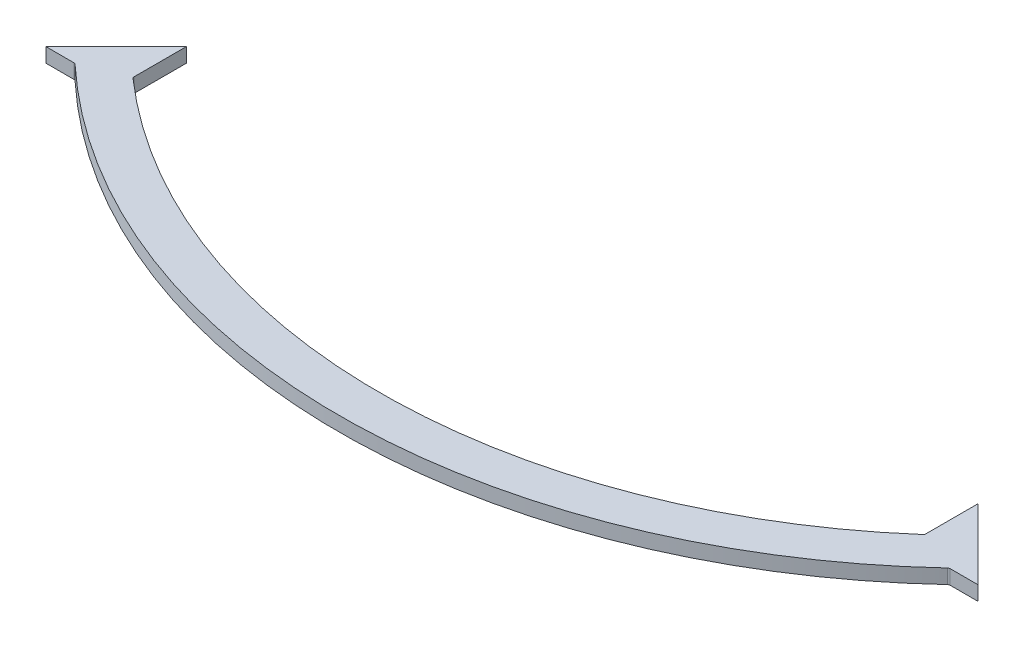
SolidWorks part; units mm, degrees
material "Pine"
ref_plane "Front Plane" through (0, 0, 0) normal (0, 0, 1) x (1, 0, 0)
ref_plane "Top Plane" through (0, 0, 0) normal (0, 1, 0) x (1, 0, 0)
ref_plane "Right Plane" through (0, 0, 0) normal (1, 0, 0) x (0, 0, -1)
sketch "Sketch1" plane through (0, 0, 0) normal (0, 1, 0) x (1, 0, 0)
  line L0 (844.55, 590.55) -> (844.55, -590.55)
  line L1 (-590.55, 862.0125) -> (590.55, 862.0125)
  line L2 (-590.55, 862.0125) -> (-590.55, -862.0125)
  line L3 (-590.55, -862.0125) -> (590.55, -862.0125)
  line L4 (590.55, 862.0125) -> (590.55, -862.0125)
  line L5 (-590.55, 862.0125) -> (590.55, -862.0125) construction
  line L6 (-590.55, -862.0125) -> (590.55, 862.0125) construction
  line L7 (-862.0125, -590.55) -> (862.0125, -590.55)
  line L8 (-862.0125, -590.55) -> (-862.0125, 590.55)
  line L9 (-862.0125, 590.55) -> (862.0125, 590.55)
  line L10 (862.0125, -590.55) -> (862.0125, 590.55)
  line L11 (-862.0125, -590.55) -> (862.0125, 590.55) construction
  line L12 (-862.0125, 590.55) -> (862.0125, -590.55) construction
  circle A0 centre (0, 0) radius 809.625
  circle A1 centre (0, 0) radius 758.825
  dimension "D1" = 1619.25
  dimension "D2" = 50.8
  dimension "D3" = 1181.1
  dimension "D4" = 862.0125
  dimension "D5" = 17.4625
sketch "Sketch2" plane through (0, 0, 0) normal (0, 1, 0) x (1, 0, 0)
  line L0 (546.1, -501.65) -> (546.1, -590.55) construction
  line L13 (590.55, -590.55) -> (501.65, -590.55)
  line L14 (590.55, -590.55) -> (590.55, -501.65)
  line L15 (590.55, -501.65) -> (501.65, -501.65)
  line L16 (501.65, -590.55) -> (501.65, -501.65)
  line L17 (590.55, 862.0125) -> (590.55, -862.0125) construction
  line L18 (501.65, -546.1) -> (590.55, -546.1) construction
  line L19 (-862.0125, -590.55) -> (862.0125, -590.55) construction
  line L20 (-501.65, -590.55) -> (-501.65, -501.65)
  line L21 (-590.55, -501.65) -> (-501.65, -501.65)
  line L22 (-590.55, -590.55) -> (-590.55, -501.65)
  line L23 (-590.55, -590.55) -> (-501.65, -590.55)
  line L24 (-501.65, -546.1) -> (-590.55, -546.1) construction
  line L25 (-546.1, -501.65) -> (-546.1, -590.55) construction
  line L26 (-590.55, 501.65) -> (-501.65, 501.65)
  line L27 (-501.65, 590.55) -> (-501.65, 501.65)
  line L28 (-590.55, 590.55) -> (-501.65, 590.55)
  line L29 (-590.55, 590.55) -> (-590.55, 501.65)
  line L30 (-546.1, 501.65) -> (-546.1, 590.55) construction
  line L31 (-501.65, 546.1) -> (-590.55, 546.1) construction
  line L32 (501.65, 590.55) -> (501.65, 501.65)
  line L33 (590.55, 501.65) -> (501.65, 501.65)
  line L34 (590.55, 590.55) -> (590.55, 501.65)
  line L35 (590.55, 590.55) -> (501.65, 590.55)
  line L36 (501.65, 546.1) -> (590.55, 546.1) construction
  line L37 (546.1, 501.65) -> (546.1, 590.55) construction
  circle A0 centre (0, 0) radius 784.225
  circle A1 centre (0, 0) radius 758.825 construction
  circle A2 centre (0, 0) radius 784.225
  circle A3 centre (0, 0) radius 784.225
  circle A4 centre (0, 0) radius 784.225
  point P24 (546.1, -546.1)
  point P48 (0, 0)
  dimension "D2" = 25.4
  dimension "D1" = 88.9
  dimension "D3" = 4
sketch "Sketch3" plane through (0, 0, 0) normal (0, 1, 0) x (1, 0, 0)
  line L0 (-501.65, -501.65) -> (-590.55, -590.55)
  line L1 (501.65, -501.65) -> (590.55, -590.55)
  line L2 (-590.55, -590.55) -> (-553.8441, -590.55)
  line L3 (-862.0125, -590.55) -> (862.0125, -590.55) construction
  line L4 (590.55, -590.55) -> (553.8441, -590.55)
  line L5 (501.65, -501.65) -> (501.65, -569.3528)
  line L6 (501.65, -590.55) -> (501.65, -501.65) construction
  line L7 (-501.65, -501.65) -> (-501.65, -569.3528)
  circle A0 centre (0, 0) radius 758.825 construction
  circle A1 centre (0, 0) radius 809.625 construction
  arc A2 (-501.65, -569.3528) -> (501.65, -569.3528) centre (0, 0) ccw
  arc A3 (-553.8441, -590.55) -> (553.8441, -590.55) centre (0, 0) ccw
extrude "Boss-Extrude1" add sketch "Sketch3" along normal blind 18.2562
sketch "Sketch4" plane through (0, 18.2562, 0) normal (0, 1, 0) x (1, 0, 0)
  line L0 (-590.55, -590.55) -> (-590.55, -501.65)
  line L1 (-590.55, -501.65) -> (-501.65, -501.65)
  line L2 (-501.65, -501.65) -> (-501.65, -590.55)
  line L3 (-501.65, -590.55) -> (-590.55, -590.55)
  line L4 (501.65, -590.55) -> (501.65, -501.65)
  line L5 (501.65, -501.65) -> (590.55, -501.65)
  line L6 (590.55, -501.65) -> (590.55, -590.55)
  line L7 (590.55, -590.55) -> (501.65, -590.55)
extrude "Boss-Extrude2" add sketch "Sketch4" against normal up to surface (18.2562 mm away) up to face at (0, 0, 614.0941)
sketch "Sketch5" plane through (0, 18.2562, 0) normal (0, 1, 0) x (1, 0, 0)
  line L8 (-590.55, -590.55) -> (-501.65, -501.65)
  line L9 (-501.65, -501.65) -> (-590.55, -501.65)
  line L10 (-590.55, -501.65) -> (-590.55, -590.55)
  line L11 (501.65, -501.65) -> (590.55, -590.55)
  line L12 (590.55, -590.55) -> (590.55, -501.65)
  line L13 (590.55, -501.65) -> (501.65, -501.65) construction
  line L14 (590.55, -590.55) -> (590.55, -501.65) construction
  line L15 (590.55, -501.65) -> (501.65, -501.65)
extrude "Cut-Extrude1" cut sketch "Sketch5" against normal through all
ref_plane "Plane1" through (0, 0, 809.625) normal (0, 0, 1) x (1, 0, 0)
fillet "Fillet1" radius 3.3782 4 edges at (-501.65, 9.1281, 569.3528) (-553.8441, 9.1281, 590.55) (501.65, 9.1281, 569.3528) (553.8441, 9.1281, 590.55)
ref_plane "Plane5" through (0, 0, 501.65) normal (0, 0, 1) x (1, 0, 0)
ref_plane "Plane6" through (-590.55, 0, 0) normal (1, 0, 0) x (0, 0, -1)
ref_plane "Plane7" through (590.55, 0, 0) normal (1, 0, 0) x (0, 0, -1)
